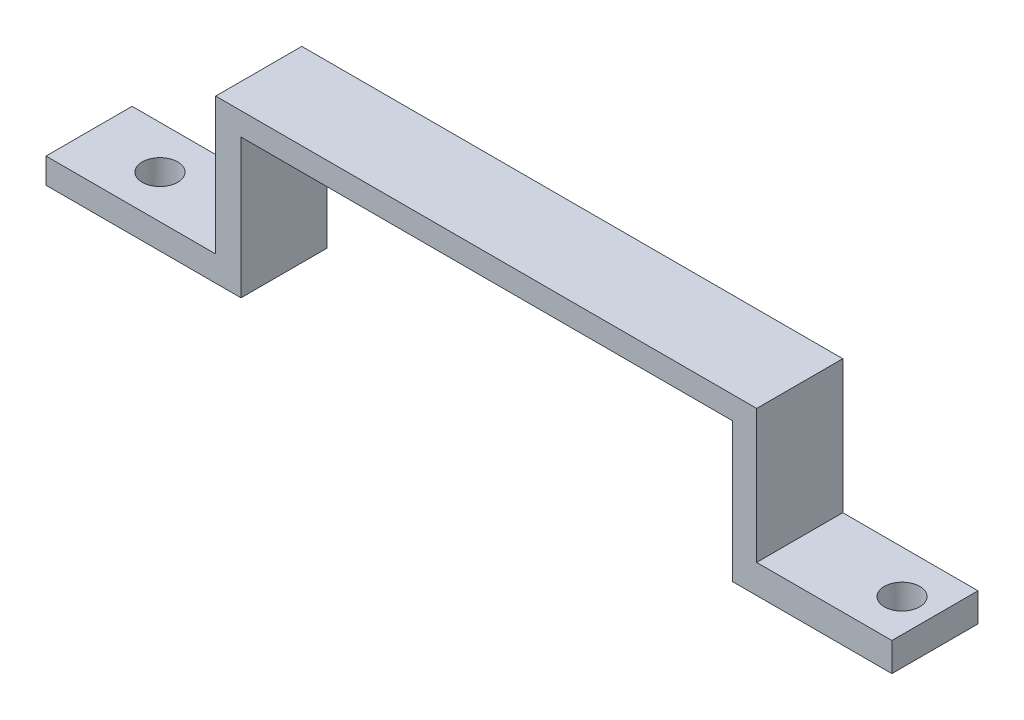
SolidWorks part; units mm, degrees
ref_plane "Front Plane" through (0, 0, 0) normal (0, 0, 1) x (1, 0, 0)
ref_plane "Top Plane" through (0, 0, 0) normal (0, 1, 0) x (1, 0, 0)
ref_plane "Right Plane" through (0, 0, 0) normal (1, 0, 0) x (0, 0, -1)
sketch "Sketch1" plane through (0, 0, 0) normal (0, 1, 0) x (1, 0, 0)
  line L1 (-132.4846, 59.9817) -> (-47.6486, 59.9817)
  line L2 (-132.4846, 59.9817) -> (-132.4846, 51.3457)
  line L3 (-132.4846, 51.3457) -> (-47.6486, 51.3457)
  line L4 (-47.6486, 59.9817) -> (-47.6486, 51.3457)
  dimension "D1" = 84.836
  dimension "D2" = 8.636
extrude "Boss-Extrude1" add sketch "Sketch1" along normal blind 16.256
sketch "Sketch2" plane through (0, 0, -51.3457) normal (0, 0, 1) x (1, 0, 0)
  line L0 (-132.4846, 0) -> (-47.6486, 0) construction
  line L1 (-112.9266, 0) -> (-63.6506, 0)
  line L2 (-112.9266, 0) -> (-112.9266, 13.97)
  line L3 (-112.9266, 13.97) -> (-63.6506, 13.97)
  line L4 (-63.6506, 0) -> (-63.6506, 13.97)
  line L5 (-47.6486, 16.256) -> (-47.6486, 0) construction
  dimension "D1" = 13.97
  dimension "D2" = 49.276
  dimension "D3" = 16.002
extrude "Cut-Extrude1" cut sketch "Sketch2" against normal through all
sketch "Sketch3" plane through (0, 16.256, 0) normal (0, 1, 0) x (1, 0, 0)
  line L0 (-125.3726, 51.3457) -> (-125.3726, 55.6637) construction
  line L1 (-132.4846, 51.3457) -> (-47.6486, 51.3457) construction
  line L2 (-125.3726, 55.6637) -> (-125.3726, 59.9817) construction
  line L3 (-47.6486, 59.9817) -> (-132.4846, 59.9817) construction
  line L4 (-63.6506, 51.3457) -> (-63.6506, 59.9817) construction
  line L5 (-47.6486, 51.3457) -> (-47.6486, 59.9817) construction
  circle A0 centre (-50.9506, 55.6637) radius 1.778
  circle A1 centre (-125.3726, 55.6637) radius 1.778
  dimension "D1" = 3.556
  dimension "D2" = 16.002
  dimension "D3" = 12.7
  dimension "D4" = 74.422
extrude "Cut-Extrude2" cut sketch "Sketch3" against normal through all
sketch "Sketch4" plane through (0, 0, -51.3457) normal (0, 0, 1) x (1, 0, 0)
  line L0 (-112.9266, 13.97) -> (-112.9266, 0) construction
  line L1 (-132.4846, 16.256) -> (-115.4666, 16.256)
  line L2 (-132.4846, 16.256) -> (-132.4846, 2.54)
  line L3 (-132.4846, 2.54) -> (-115.4666, 2.54)
  line L4 (-115.4666, 16.256) -> (-115.4666, 2.54)
  line L5 (-47.6486, 16.256) -> (-61.2104, 16.256)
  line L6 (-47.6486, 16.256) -> (-47.6486, 2.8797)
  line L7 (-47.6486, 2.8797) -> (-61.2104, 2.8797)
  line L8 (-61.2104, 16.256) -> (-61.2104, 2.8797)
  line L9 (-132.4846, 0) -> (-112.9266, 0) construction
  dimension "D1" = 2.54
  dimension "D2" = 2.54
extrude "Cut-Extrude3" cut sketch "Sketch4" against normal through all
